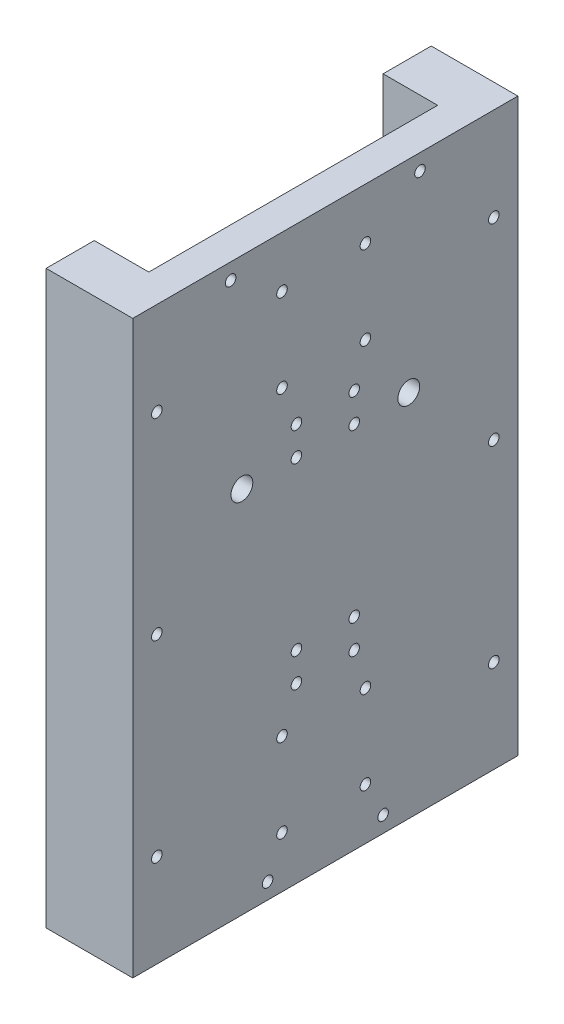
SolidWorks part; units mm, degrees
ref_plane "前视基准面" through (0, 0, 0) normal (0, 0, 1) x (1, 0, 0)
ref_plane "上视基准面" through (0, 0, 0) normal (0, 1, 0) x (1, 0, 0)
ref_plane "右视基准面" through (0, 0, 0) normal (1, 0, 0) x (0, 0, -1)
other "Configuration Table"
sketch "草图1" plane through (0, 0, 0) normal (1, 0, 0) x (0, 0, -1)
  line L1 (0, 0) -> (120, 0)
  line L2 (0, 0) -> (0, 178)
  line L3 (0, 178) -> (120, 178)
  line L4 (120, 0) -> (120, 178)
  dimension "D1" = 120
  dimension "D2" = 178
extrude "凸台-拉伸1" add sketch "草图1" along normal blind 10
sketch "草图2" plane through (0, 0, 0) normal (-1, 0, 0) x (0, 0, 1)
  line L0 (-120, 0) -> (-120, 178) construction
  line L1 (-120, 178) -> (-105, 178)
  line L2 (-120, 178) -> (-120, 0)
  line L3 (-120, 0) -> (-105, 0)
  line L4 (-105, 178) -> (-105, 0)
  line L5 (0, 0) -> (-120, 0) construction
  line L6 (-120, 178) -> (0, 178) construction
  line L7 (0, 178) -> (-15, 178)
  line L8 (0, 178) -> (0, 0)
  line L9 (0, 0) -> (-15, 0)
  line L10 (-15, 178) -> (-15, 0)
  line L11 (0, 178) -> (0, 0) construction
  dimension "D1" = 15
  dimension "D2" = 15
  dimension "D3" = 178
extrude "凸台-拉伸2" add sketch "草图2" along normal blind 17
sketch "草图3" plane through (0, 0, 0) normal (-1, 0, 0) x (0, 0, 1)
  line L0 (-105, 178) -> (-15, 178) construction
  line L1 (-95, 127) -> (-25, 127)
  line L2 (-95, 127) -> (-95, 103)
  line L3 (-95, 103) -> (-25, 103)
  line L4 (-25, 127) -> (-25, 103)
  line L5 (-60, 178) -> (-60, 146.8058) construction
  dimension "D1" = 70
  dimension "D2" = 75
  dimension "D3" = 24
extrude "切除-拉伸1" cut sketch "草图3" against normal blind 5
sketch "草图4" plane through (-17, 0, 0) normal (-1, 0, 0) x (0, 0, 1)
  circle A0 centre (-112.5, 149) radius 2.25
  circle A1 centre (-7.5, 149) radius 2.25
hole_wizard "M4 螺纹孔1" positions "3D草图1" profile "草图5" tap size "M4" standard "GB" end condition through all
sketch3d "3D草图1"
  point P0 (-17, 149, -112.5)
  point P3 (-17, 149, -7.5)
sketch "草图5" plane through (-17, 149, -112.5) normal (0, 1, 0) x (0, 0, 1)
  line L0 (0, 0) -> (0, 27)
  line L1 (0, 27) -> (1.65, 27)
  line L2 (1.65, 27) -> (1.65, 0)
  line L5 (1.65, 0) -> (0, 0)
  line L11 (0, -6.35) -> (0, 107.95) construction
  dimension "通孔螺纹孔钻头直径" = 3.3
  dimension "通孔螺纹孔钻头深度" = 27
cosmetic thread "孔螺蚊线32" parameters "D1"=8, "D2"=4.3
cosmetic thread "孔螺蚊线33" parameters "D1"=8, "D2"=4.3
pattern_linear "阵列(线性)1" count 3 spacing 60 along (0, -1, 0) of "M4 螺纹孔1"
sketch "草图6" plane through (0, 0, 0) normal (-1, 0, 0) x (0, 0, 1)
  circle A0 centre (-89.5, 173) radius 2.25
  circle A1 centre (-30.5, 173) radius 2.25
  circle A2 centre (-86, 115) radius 4.5
  circle A3 centre (-34, 115) radius 4.5
  circle A4 centre (-78, 5) radius 2.25
  circle A5 centre (-42, 5) radius 2.25
hole_wizard "M4 螺纹孔2" positions "3D草图2" profile "草图7" tap size "M4" standard "GB" end condition through all
sketch3d "3D草图2"
  point P0 (0, 173, -89.5)
  point P3 (0, 173, -30.5)
  point P6 (0, 5, -78)
  point P9 (0, 5, -42)
sketch "草图7" plane through (0, 173, -89.5) normal (0, 1, 0) x (0, 0, 1)
  line L0 (0, 0) -> (0, 10)
  line L1 (0, 10) -> (1.65, 10)
  line L2 (1.65, 10) -> (1.65, 0)
  line L5 (1.65, 0) -> (0, 0)
  line L11 (0, -6.35) -> (0, 107.95) construction
  dimension "通孔螺纹孔钻头直径" = 3.3
  dimension "通孔螺纹孔钻头深度" = 10
cosmetic thread "孔螺蚊线3" parameters "D2"=4
cosmetic thread "孔螺蚊线4" parameters "D2"=4
cosmetic thread "孔螺蚊线5" parameters "D2"=4
cosmetic thread "孔螺蚊线6" parameters "D2"=4
hole_wizard "M8 螺纹孔1" positions "3D草图3" profile "草图8" tap size "M8" standard "GB" end condition through all
sketch3d "3D草图3"
  point P0 (0, 115, -86)
  point P3 (0, 115, -34)
sketch "草图8" plane through (0, 115, -86) normal (0, 1, 0) x (0, 0, 1)
  line L0 (0, 0) -> (0, 10)
  line L1 (0, 10) -> (3.4, 10)
  line L2 (3.4, 10) -> (3.4, 0)
  line L5 (3.4, 0) -> (0, 0)
  line L11 (0, -6.35) -> (0, 107.95) construction
  dimension "通孔螺纹孔钻头直径" = 6.8
  dimension "通孔螺纹孔钻头深度" = 10
cosmetic thread "孔螺蚊线8" parameters "D2"=8
cosmetic thread "孔螺蚊线31" parameters "D2"=8
sketch "草图14" plane through (0, 0, 0) normal (-1, 0, 0) x (0, 0, 1)
  line L0 (-69, 115) -> (-69, 63) construction
  line L1 (-69, 89) -> (-25.8375, 89) construction
  circle A0 centre (-69, 115) radius 2
  circle A1 centre (-51, 115) radius 2
  circle A2 centre (-69, 54) radius 2
  circle A3 centre (-51, 54) radius 2
  circle A4 centre (-51, 63) radius 2
  circle A5 centre (-69, 63) radius 2
  circle A6 centre (-51, 124) radius 2
  circle A7 centre (-69, 124) radius 2
hole_wizard "M4 螺纹孔7" positions "3D草图7" profile "草图16" tap size "M4" standard "GB" end condition through all
sketch3d "3D草图7"
  point P0 (0, 115, -69)
  point P3 (0, 115, -51)
  point P6 (0, 124, -69)
  point P9 (0, 124, -51)
sketch "草图16" plane through (0, 115, -69) normal (0, 1, 0) x (0, 0, 1)
  line L0 (0, 0) -> (0, 10)
  line L1 (0, 10) -> (1.65, 10)
  line L2 (1.65, 10) -> (1.65, 0)
  line L5 (1.65, 0) -> (0, 0)
  line L11 (0, -6.35) -> (0, 107.95) construction
  dimension "通孔螺纹孔钻头直径" = 3.3
  dimension "通孔螺纹孔钻头深度" = 10
hole_wizard "M4 螺纹孔3" positions "3D草图8" profile "草图17" tap size "M4" standard "GB" end condition through all
sketch3d "3D草图8"
  point P0 (0, 63, -69)
  point P3 (0, 63, -51)
  point P6 (0, 54, -69)
  point P9 (0, 54, -51)
sketch "草图17" plane through (0, 63, -69) normal (0, 1, 0) x (0, 0, 1)
  line L0 (0, 0) -> (0, 10)
  line L1 (0, 10) -> (1.65, 10)
  line L2 (1.65, 10) -> (1.65, 0)
  line L5 (1.65, 0) -> (0, 0)
  line L11 (0, -6.35) -> (0, 107.95) construction
  dimension "通孔螺纹孔钻头直径" = 3.3
  dimension "通孔螺纹孔钻头深度" = 10
cosmetic thread "孔螺蚊线17" parameters "D1"=8, "D2"=4.3
cosmetic thread "孔螺蚊线18" parameters "D1"=8, "D2"=4.3
cosmetic thread "孔螺蚊线19" parameters "D1"=8, "D2"=4.3
cosmetic thread "孔螺蚊线20" parameters "D1"=8, "D2"=4.3
sketch "草图18" plane through (0, 0, 0) normal (-1, 0, 0) x (0, 0, 1)
  line L0 (-120, 89) -> (12.8421, 89) construction
  line L1 (-120, 178) -> (-120, 0) construction
  circle A0 centre (-72.5, 162) radius 1.621
  circle A1 centre (-46.5, 162) radius 1.621
  circle A2 centre (-46.5, 136) radius 1.621
  circle A3 centre (-72.5, 136) radius 1.621
  circle A4 centre (-72.5, 42) radius 1.621
  circle A5 centre (-46.5, 42) radius 1.621
  circle A6 centre (-46.5, 16) radius 1.621
  circle A7 centre (-72.5, 16) radius 1.621
hole_wizard "M4 螺纹孔5" positions "3D草图10" profile "草图20" tap size "M4" standard "GB"
sketch3d "3D草图10"
  point P0 (0, 162, -72.5)
  point P11 (0, 162, -46.5)
  point P14 (0, 136, -41.5)
  point P16 (0, 136, -67.5)
  point P18 (0, 16, -72.5)
  point P21 (0, 16, -46.5)
  point P24 (0, 42, -46.5)
  point P27 (0, 42, -72.5)
sketch "草图20" plane through (0, 162, -72.5) normal (0, 1, 0) x (0, 0, 1)
  line L0 (0, 0) -> (0, 10)
  line L1 (0, 10) -> (1.65, 10)
  line L2 (1.65, 10) -> (1.65, 0)
  line L5 (1.65, 0) -> (0, 0)
  line L11 (0, -6.35) -> (0, 107.95) construction
  dimension "通孔螺纹孔钻头直径" = 3.3
  dimension "通孔螺纹孔钻头深度" = 10
cosmetic thread "孔螺蚊线21" parameters "D2"=4
cosmetic thread "孔螺蚊线22" parameters "D2"=4
cosmetic thread "孔螺蚊线24" parameters "D2"=4
cosmetic thread "孔螺蚊线25" parameters "D2"=4
cosmetic thread "孔螺蚊线27" parameters "D2"=4
cosmetic thread "孔螺蚊线28" parameters "D2"=4
hole_wizard "M4 螺纹孔6" positions "3D草图11" profile "草图21" tap size "M4" standard "GB" end condition through all
sketch3d "3D草图11"
  point P0 (0, 136, -72.5)
  point P3 (0, 136, -46.5)
sketch "草图21" plane through (0, 136, -72.5) normal (0, 1, 0) x (0, 0, 1)
  line L0 (0, 0) -> (0, 10)
  line L1 (0, 10) -> (1.65, 10)
  line L2 (1.65, 10) -> (1.65, 0)
  line L5 (1.65, 0) -> (0, 0)
  line L11 (0, -6.35) -> (0, 107.95) construction
  dimension "通孔螺纹孔钻头直径" = 3.3
  dimension "通孔螺纹孔钻头深度" = 10
cosmetic thread "孔螺蚊线29" parameters "D2"=4
cosmetic thread "孔螺蚊线30" parameters "D2"=4
